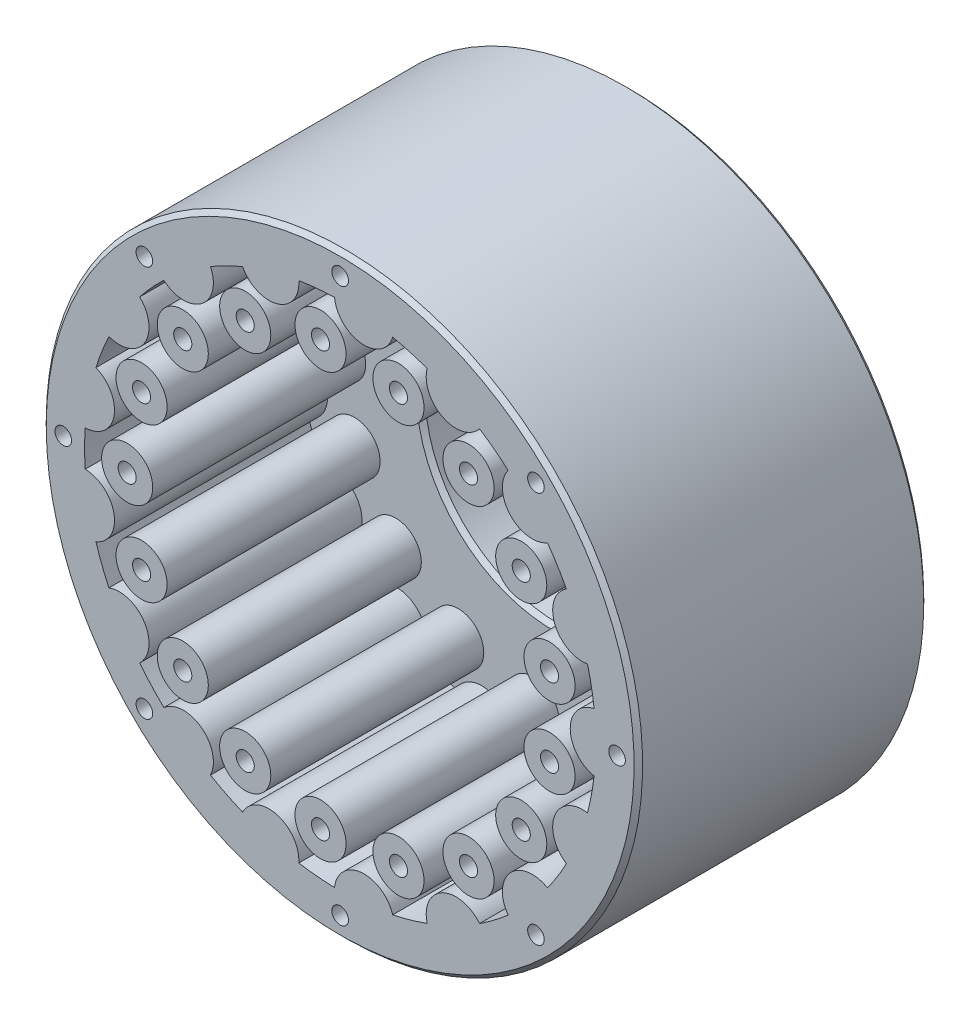
SolidWorks part; units mm, degrees
ref_plane "Front Plane" through (0, 0, 0) normal (0, 0, 1) x (1, 0, 0)
ref_plane "Top Plane" through (0, 0, 0) normal (0, 1, 0) x (1, 0, 0)
ref_plane "Right Plane" through (0, 0, 0) normal (1, 0, 0) x (0, 0, -1)
sketch "Sketch3" plane through (0, 0, 0) normal (0, 0, 1) x (1, 0, 0)
  circle A0 centre (0, 0) radius 60
  dimension "D1" = 120
extrude "Housing Base" add sketch "Sketch3" along normal mid plane 18
sketch "Sketch2" plane through (0, 0, 9) normal (0, 0, 1) x (1, 0, 0)
  circle A0 centre (0, 0) radius 50 construction
  circle A1 centre (-50, 0) radius 6
  dimension "D1" = 100
  dimension "D2" = 12
extrude "Rollers" add sketch "Sketch2" along normal blind 50 separate body
pattern_circular "Roller Body Pattern" count 17 over 360 about axis through (0, 0, 0) along (0, 0, 1) of "Rollers"
extrude "Dowel Holes" cut sketch "Sketch10" against normal blind 55
sketch "Sketch10" plane through (0, 0, 59) normal (0, 0, 1) x (1, 0, 0)
  circle A0 centre (-50, 0) radius 2.125
  circle A1 centre (-50, 0) radius 6 construction
  dimension "D1" = 4.25
pattern_circular "Dowel Hole Pattern" count 17 over 360 about axis through (0, 0, 0) along (0, 0, 1) of "Dowel Holes"
sketch "Sketch5" plane through (0, 0, 9) normal (0, 0, 1) x (1, 0, 0)
  circle A0 centre (-50, 0) radius 3.15
  dimension "D1" = 6.3
extrude "Roller Hole" cut sketch "Sketch5" against normal blind 0.5
pattern_circular "CirPattern2" count 17 over 360 about axis through (0, 0, 0) along (0, 0, 1) of "Roller Hole"
sketch "Sketch4" plane through (0, 0, -9) normal (0, 0, -1) x (-1, 0, 0)
  circle A0 centre (0, 0) radius 31.05
  dimension "D1" = 62.1
extrude "Center Hole" cut sketch "Sketch4" along normal blind 14 from surface at -18 starting at face at (-43.6863, 16.9242, 9)
sketch "Sketch6" plane through (0, 0, -5) normal (0, 0, 1) x (1, 0, 0)
  circle A1 centre (0, 0) radius 18
  dimension "D1" = 36
extrude "OutputShaft Hole" cut sketch "Sketch6" against normal through all
sketch "Sketch7" plane through (0, 0, -9) normal (0, 0, -1) x (-1, 0, 0)
  line L0 (-13.6831, 48.0913) -> (-5.6289, 60.7455) construction
  line L1 (4.6134, 49.7867) -> (-5.6289, 60.7455) construction
  arc A1 (1.3297, 59.9853) -> (-12.3293, 58.7196) centre (-5.6289, 60.7455) cw
  circle A2 centre (0, 0) radius 60 construction
  circle A3 centre (4.6134, 49.7867) radius 6 construction
  arc A4 (22.9091, 55.4543) -> (9.7152, 59.2082) centre (16.695, 58.6769) cw
  circle A5 centre (4.6134, 49.7867) radius 6 construction
  arc A6 (41.3945, 43.4338) -> (30.4476, 51.7005) centre (36.7642, 48.6836) cw
  arc A7 (54.2893, 25.5474) -> (47.068, 37.2103) centre (51.8681, 32.1154) cw
  arc A8 (59.8521, 4.2107) -> (57.3315, 17.6947) centre (59.967, 11.2098) cw
  arc A9 (57.3315, -17.6947) -> (59.8521, -4.2107) centre (59.967, -11.2098) cw
  arc A10 (47.068, -37.2103) -> (54.2893, -25.5474) centre (51.8681, -32.1154) cw
  arc A11 (30.4476, -51.7005) -> (41.3945, -43.4338) centre (36.7642, -48.6836) cw
  arc A12 (9.7152, -59.2082) -> (22.9091, -55.4543) centre (16.695, -58.6769) cw
  arc A13 (-12.3293, -58.7196) -> (1.3297, -59.9853) centre (-5.6289, -60.7455) cw
  arc A14 (-32.7087, -50.3005) -> (-20.4293, -56.4149) centre (-27.1926, -54.6101) cw
  arc A15 (-48.6706, -35.0881) -> (-39.4292, -45.2255) centre (-45.0838, -41.0993) cw
  arc A16 (-58.0593, -15.1368) -> (-53.1039, -27.928) centre (-56.8862, -22.0378) cw
  arc A17 (-59.6067, 6.8588) -> (-59.6067, -6.8588) centre (-61.0057, 0) cw
  arc A18 (-53.1039, 27.928) -> (-58.0593, 15.1368) centre (-56.8862, 22.0378) cw
  arc A19 (-39.4292, 45.2255) -> (-48.6706, 35.0881) centre (-45.0838, 41.0993) cw
  arc A20 (-20.4293, 56.4149) -> (-32.7087, 50.3005) centre (-27.1926, 54.6101) cw
  circle A22 centre (0, 0) radius 60
  circle A23 centre (0, 0) radius 70
  circle A24 centre (0, 0) radius 70
  circle A25 centre (4.6134, 49.7867) radius 6 construction
  point P62 (0, 0)
  dimension "D1" = 15
  dimension "D2" = 7
  dimension "D4" = 10
  dimension "D3" = 17
extrude "OuterWall" add sketch "Sketch7" against normal blind 68
hole_wizard "Ø4.0mm Screw Hole1" positions "Sketch8" profile "Sketch9" hole size "Ø4.0" standard "ANSI Metric"
sketch "Sketch8" plane through (0, 0, 59) normal (0, 0, 1) x (1, 0, 0)
  circle A0 centre (0, 0) radius 65 construction
  point P7 (-65, 0)
  dimension "D1" = 130
sketch "Sketch9" plane through (-65, 0, 59) normal (1, 0, 0) x (0, -1, 0)
  line L0 (0, 0) -> (0, 50)
  line L1 (0, 50) -> (1.95, 50)
  line L2 (1.95, 50) -> (1.95, 0)
  line L5 (1.95, 0) -> (0, 0)
  line L10 (0, 50) -> (-1.95, 50) construction
  line L11 (0, -6.35) -> (0, 107.95) construction
  dimension "Hole Dia." = 3.9
  dimension "Hole Depth" = 50
  dimension "Drill Angle" = 180
pattern_circular "CirPattern3" count 8 over 360 about axis through (0, 0, 0) along (0, 0, 1) of "Ø4.0mm Screw Hole1"
sketch "Sketch11" plane through (0, 0, -9) normal (0, 0, -1) x (-1, 0, 0)
  line L1 (-12.5, 36) -> (12.5, 36) construction
  line L2 (-12.5, 36) -> (-12.5, -36) construction
  line L3 (-12.5, -36) -> (12.5, -36) construction
  line L4 (12.5, 36) -> (12.5, -36) construction
  line L5 (-12.5, 36) -> (12.5, -36) construction
  line L6 (-12.5, -36) -> (12.5, 36) construction
  line L7 (-36, 12.5) -> (36, 12.5) construction
  line L8 (-36, 12.5) -> (-36, -12.5) construction
  line L9 (-36, -12.5) -> (36, -12.5) construction
  line L10 (36, 12.5) -> (36, -12.5) construction
  line L11 (-36, 12.5) -> (36, -12.5) construction
  line L12 (-36, -12.5) -> (36, 12.5) construction
  circle A0 centre (-12.5, 36) radius 2.85
  circle A1 centre (12.5, 36) radius 2.85
  circle A2 centre (36, 12.5) radius 2.85
  circle A3 centre (36, -12.5) radius 2.85
  circle A4 centre (12.5, -36) radius 2.85
  circle A5 centre (-12.5, -36) radius 2.85
  circle A6 centre (-36, -12.5) radius 2.85
  circle A7 centre (-36, 12.5) radius 2.85
  circle A8 centre (-36, 0) radius 2.85
  circle A9 centre (0, 36) radius 2.85
  circle A10 centre (36, 0) radius 2.85
  circle A11 centre (0, -36) radius 2.85
  point P0 (0, 0)
  point P5 (0, 0)
  dimension "D3" = 5.7
  dimension "D1" = 72
  dimension "D2" = 25
extrude "BackThreadedInserts" cut sketch "Sketch11" against normal blind 6
chamfer "Chamfer1" distance 1 angle 45 5 edges at (18, 0, -9) (18, 0, -5) (31.05, 0, 9) (-70, 0, 59) (-70, 0, -9)
delete or keep bodies "Body-Delete/Keep 1" [suppressed] bodies 128 184 183 182 181 180 179 178 177 176 175 174 173 172 171 170 169
equation "\"Roller Construction Circle\"= 100mm"
equation "\"Roller Diameter\"= 12mm"
equation "\"D2@Sketch2\"=\"Roller Diameter\""
equation "\"D1@Sketch2\"=\"Roller Construction Circle\""
